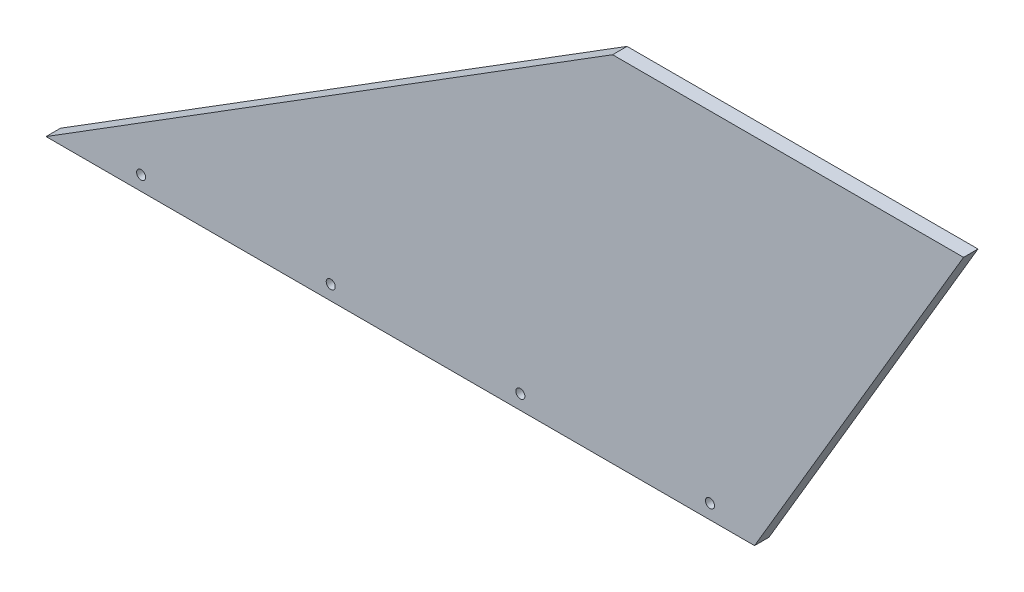
SolidWorks part; units mm, degrees
ref_plane "Front Plane" through (0, 0, 0) normal (0, 0, 1) x (1, 0, 0)
ref_plane "Top Plane" through (0, 0, 0) normal (0, 1, 0) x (1, 0, 0)
ref_plane "Right Plane" through (0, 0, 0) normal (1, 0, 0) x (0, 0, -1)
sketch "Sketch1" plane through (0, 0, 0) normal (0, 0, 1) x (1, 0, 0)
  line L0 (-59.8854, 149.4472) -> (-298.958, 0)
  line L1 (-298.958, 0) -> (0, 0)
  line L2 (-59.8854, 149.4472) -> (88.1966, 149.4472)
  line L3 (88.1966, 149.4472) -> (0, 0)
  dimension "D1" = 281.94
  dimension "D2" = 148.082
  dimension "D3" = 147.99
  dimension "D4" = 298.958
extrude "Boss-Extrude1" add sketch "Sketch1" along normal mid plane 6.096
hole_wizard "Hole1" positions "Sketch2" profile "Sketch3" legacy
sketch "Sketch2" plane through (0, 0, 3.048) normal (0, 0, 1) x (1, 0, 0)
  line L0 (-298.958, 0) -> (0, 0) construction
  point P0 (-258.826, 6.096)
  dimension "D1" = 40.132
  dimension "D2" = 6.096
sketch "Sketch3" plane through (-258.826, 6.096, 3.048) normal (1, 0, 0) x (0, -1, 0)
  line L0 (0, 0) -> (0, 15.24)
  line L1 (0, 15.24) -> (1.905, 15.24)
  line L2 (1.905, 15.24) -> (1.905, 0)
  line L3 (1.905, 0) -> (0, 0)
  line L4 (0, 110) -> (0, -10) construction
  dimension "Diameter" = 3.81
  dimension "Depth" = 15.24
pattern_linear "LPattern1" count 4 spacing 80.01 along (1, 0, 0) of "Hole1"
